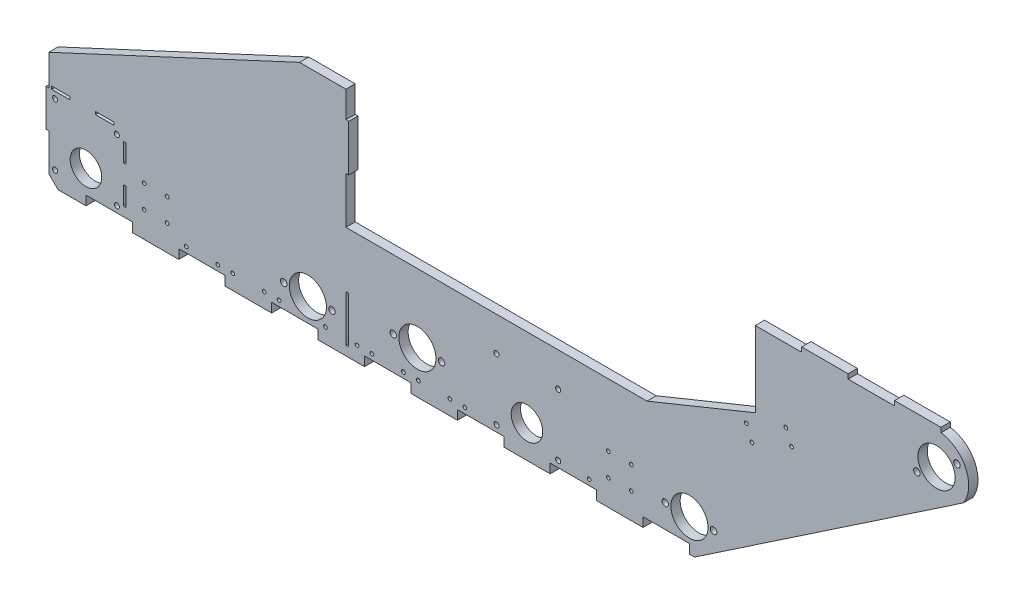
SolidWorks part; units mm, degrees
material "아크릴(내충격성)"
ref_plane "정면" through (0, 0, 0) normal (0, 0, 1) x (1, 0, 0)
ref_plane "윗면" through (0, 0, 0) normal (0, 1, 0) x (1, 0, 0)
ref_plane "우측면" through (0, 0, 0) normal (1, 0, 0) x (0, 0, -1)
sketch "스케치1" plane through (0, 0, 0) normal (0, 0, 1) x (1, 0, 0)
  line L0 (35.3016, 38.2586) -> (35.3016, -130.1494) construction
  line L3 (5.2676, -97.6555) -> (35.3016, -97.6555)
  line L5 (-42.9653, -47.6555) -> (113.7321, -47.6555) construction
  line L6 (-13.0327, -95.9898) -> (35.3016, -47.6555) construction
  line L7 (360.3016, 61.656) -> (360.3016, -136.4824) construction
  line L10 (685.3016, -62.6555) -> (510.3016, -62.6555) construction
  line L11 (510.3016, -62.6555) -> (470.1121, -62.6555) construction
  line L12 (652.0676, -14.4224) -> (652.0676, -80.8905) construction
  line L13 (2.0676, -14.4224) -> (2.0676, -80.8905) construction
  line L14 (510.3016, -62.6555) -> (951.4227, 116.8455) construction
  line L15 (639.5932, 22.3445) -> (956.2142, 151.1839)
  line L16 (685.3016, -62.6555) -> (951.4227, 116.8455) construction
  line L17 (35.3016, -62.6555) -> (274.3016, -62.6555) construction
  line L18 (274.3016, -62.6555) -> (392.3016, -62.6555) construction
  line L19 (392.3016, -62.6555) -> (392.3016, -51.6555) construction
  line L20 (347.1794, -51.6555) -> (433.0872, -51.6555) construction
  line L22 (718.5356, -14.4224) -> (456.239, -14.4224) construction
  line L23 (-14.6984, -87.6555) -> (705.4567, -87.6555) construction
  line L24 (685.3016, -62.6555) -> (722.4102, -62.6555) construction
  line L25 (980.3852, 97.7862) -> (690.6311, -97.6555)
  line L26 (35.3016, -97.6555) -> (35.3016, -87.6555)
  line L27 (231.5316, 22.3445) -> (231.5316, -97.6555) construction
  line L28 (35.3016, -87.6555) -> (85.3016, -87.6555)
  line L29 (182.7916, 22.3445) -> (182.7916, -87.6555) construction
  line L30 (85.3016, -87.6555) -> (85.3016, -97.6555)
  line L34 (135.3016, -97.6555) -> (135.3016, -87.6555)
  line L38 (231.5316, -97.6555) -> (235.3016, -97.6555)
  line L39 (135.2976, -97.6555) -> (135.3016, -97.6555)
  line L40 (135.3016, -87.6555) -> (185.3016, -87.6555)
  line L41 (185.3016, -87.6555) -> (185.3016, -97.6555)
  line L42 (85.3056, -97.6555) -> (135.2976, -97.6555)
  line L43 (185.3016, -97.6555) -> (231.5316, -97.6555)
  line L44 (235.3016, -97.6555) -> (235.3016, -87.6555)
  line L45 (235.3016, -87.6555) -> (285.3016, -87.6555)
  line L46 (285.3016, -87.6555) -> (285.3016, -97.6555)
  line L47 (335.3016, -97.6555) -> (335.3016, -87.6555)
  line L48 (335.3016, -87.6555) -> (385.3016, -87.6555)
  line L49 (385.3016, -87.6555) -> (385.3016, -97.6555)
  line L50 (435.3016, -97.6555) -> (435.3016, -87.6555)
  line L51 (435.3016, -87.6555) -> (485.3016, -87.6555)
  line L52 (485.3016, -87.6555) -> (485.3016, -97.6555)
  line L53 (535.3016, -97.6555) -> (535.3016, -87.6555)
  line L54 (535.3016, -87.6555) -> (585.3016, -87.6555)
  line L55 (585.3016, -87.6555) -> (585.3016, -97.6555)
  line L56 (635.3016, -97.6555) -> (635.3016, -87.6555)
  line L57 (635.3016, -87.6555) -> (685.3016, -87.6555)
  line L58 (685.3016, -87.6555) -> (685.3016, -97.6555)
  line L59 (85.3016, -97.6555) -> (85.3056, -97.6555)
  line L60 (285.3016, -97.6555) -> (335.3016, -97.6555)
  line L61 (385.3016, -97.6555) -> (435.3016, -97.6555)
  line L62 (485.3016, -97.6555) -> (535.3016, -97.6555)
  line L63 (585.3016, -97.6555) -> (635.3016, -97.6555)
  line L64 (685.3016, -97.6555) -> (690.6311, -97.6555)
  line L65 (-25.5762, -81.6555) -> (758.4959, -81.6555) construction
  line L66 (110.3016, -97.6555) -> (110.3016, -39.5812) construction
  line L71 (110.3016, -57.6555) -> (92.8016, -57.6555) construction
  line L72 (110.3016, -57.6555) -> (97.9272, -45.2811) construction
  line L73 (610.3016, -97.6555) -> (610.3016, -39.5812) construction
  line L74 (610.3016, -57.6555) -> (592.8016, -57.6555) construction
  line L75 (610.3016, -57.6555) -> (597.9272, -45.2811) construction
  line L76 (-14.6984, -7.4224) -> (81.4007, -7.4224) construction
  line L77 (75.5356, -87.6555) -> (75.5356, 5.7003) construction
  line L78 (315.3016, 122.6616) -> (315.3016, 146.501)
  line L79 (-11.6984, -97.6555) -> (-11.6984, -7.4224) construction
  line L87 (315.3016, -97.6555) -> (315.3016, 22.3445) construction
  line L88 (-1.6984, -7.4224) -> (18.3016, -7.4224)
  line L89 (-1.6984, -7.4224) -> (-1.6984, -4.4224)
  line L90 (-1.6984, -4.4224) -> (18.3016, -4.4224)
  line L91 (18.3016, -7.4224) -> (18.3016, -4.4224)
  line L92 (65.5356, -7.4224) -> (45.5356, -7.4224)
  line L93 (65.5356, -7.4224) -> (65.5356, -4.4224)
  line L94 (65.5356, -4.4224) -> (45.5356, -4.4224)
  line L95 (45.5356, -7.4224) -> (45.5356, -4.4224)
  line L96 (75.5356, -17.4224) -> (78.6964, -17.4224)
  line L97 (75.5356, -17.4224) -> (75.5356, -37.4224)
  line L98 (75.5356, -37.4224) -> (78.6964, -37.4224)
  line L99 (78.6964, -17.4224) -> (78.6964, -37.4224)
  line L100 (75.5356, -77.6555) -> (78.6964, -77.6555)
  line L101 (75.5356, -77.6555) -> (75.5356, -57.6555)
  line L102 (75.5356, -57.6555) -> (78.6964, -57.6555)
  line L103 (78.6964, -77.6555) -> (78.6964, -57.6555)
  line L104 (321.0516, -97.6555) -> (321.0516, -72.2502) construction
  line L105 (315.3016, 22.3445) -> (315.3016, 151.1839) construction
  line L114 (315.3016, 151.1839) -> (956.2142, 151.1839) construction
  line L115 (315.3016, 22.3445) -> (315.3016, 72.6616)
  line L118 (315.3016, 22.3445) -> (639.5932, 22.3445)
  line L121 (315.3016, -87.6555) -> (318.3016, -87.6555)
  line L122 (315.3016, -87.6555) -> (315.3016, -37.6555)
  line L123 (315.3016, -37.6555) -> (318.3016, -37.6555)
  line L124 (318.3016, -87.6555) -> (318.3016, -37.6555)
  line L125 (315.3016, 72.6616) -> (318.3016, 72.6616)
  line L127 (315.3016, 122.6616) -> (318.3016, 122.6616)
  line L128 (318.3016, 72.6616) -> (318.3016, 122.6616)
  line L130 (315.3016, 146.501) -> (315.3016, 151.1839)
  line L131 (315.3016, 151.1839) -> (265.2997, 151.1839)
  line L132 (265.2997, 151.1839) -> (-4.7324, 25.5846)
  line L133 (-4.7324, -97.6555) -> (-4.7324, 25.5846) construction
  line L135 (-4.7324, -87.6555) -> (5.2676, -97.6555)
  line L136 (-7.7324, -97.6555) -> (-7.7324, 24.1892) construction
  line L139 (-4.7324, -87.6555) -> (-4.7324, -47.6895)
  line L140 (-4.7324, -47.6895) -> (-7.7324, -47.6895)
  line L141 (-7.7324, -47.6895) -> (-7.7324, -7.6895)
  line L142 (-7.7324, -7.6895) -> (-4.7324, -7.6895)
  line L143 (-4.7324, -7.6895) -> (-4.7324, 25.5846)
  circle A1 centre (2.0676, -80.8905) radius 2.75
  circle A5 centre (2.0676, -14.4224) radius 2.75
  circle A6 centre (68.5356, -14.4224) radius 2.75
  circle A7 centre (68.5356, -80.8905) radius 2.75
  circle A12 centre (35.3016, -62.6555) radius 17
  circle A13 centre (685.3016, -62.6555) radius 20
  circle A14 centre (951.4227, 116.8455) radius 20
  circle A15 centre (973.4042, 130.7311) radius 3.5
  circle A16 centre (930.3015, 101.6831) radius 3.5
  arc A18 (980.3852, 97.7862) -> (956.2142, 151.1839) centre (951.4227, 116.8455) ccw
  circle A22 centre (274.3016, -62.6555) radius 20
  circle A23 centre (248.3016, -62.6555) radius 3.5
  circle A24 centre (300.3016, -62.6555) radius 3.5
  circle A25 centre (392.3016, -51.6555) radius 20
  circle A26 centre (366.3016, -51.6555) radius 3.5
  circle A27 centre (418.3016, -51.6555) radius 3.5
  circle A28 centre (543.8987, -14.4224) radius 2.75
  circle A29 centre (477.4307, -14.4224) radius 2.75
  circle A30 centre (477.4307, -80.8905) radius 2.75
  circle A31 centre (543.8987, -80.8905) radius 2.75
  circle A32 centre (510.3016, -62.6555) radius 17
  circle A33 centre (659.3016, -62.6555) radius 3.5
  circle A34 centre (711.3016, -62.6555) radius 3.5
  circle A37 centre (143.3016, -81.6555) radius 2
  circle A38 centre (177.3016, -81.6555) radius 2
  circle A39 centre (193.3016, -81.6555) radius 2
  circle A40 centre (227.3016, -81.6555) radius 2
  circle A41 centre (243.3016, -81.6555) radius 2
  circle A43 centre (293.3016, -81.6555) radius 2
  circle A44 centre (327.3016, -81.6555) radius 2
  circle A45 centre (343.3016, -81.6555) radius 2
  circle A46 centre (377.3016, -81.6555) radius 2
  circle A47 centre (393.3016, -81.6555) radius 2
  circle A48 centre (427.3016, -81.6555) radius 2
  circle A49 centre (443.3016, -81.6555) radius 2
  circle A54 centre (577.3016, -81.6555) radius 2
  circle A67 centre (97.9272, -45.2811) radius 2
  circle A68 centre (122.676, -45.2811) radius 2
  circle A69 centre (122.676, -70.0298) radius 2
  circle A70 centre (97.9272, -70.0298) radius 2
  circle A72 centre (597.9272, -45.2811) radius 2
  circle A73 centre (622.676, -45.2811) radius 2
  circle A74 centre (622.676, -70.0298) radius 2
  circle A75 centre (597.9272, -70.0298) radius 2
  point P22 (28.6519, -47.9736)
  point P25 (35.3016, -47.6565)
  point P53 (730.8621, 27.095)
  dimension "D3" = 175
  dimension "D5" = 4
  dimension "D9" = 34
  dimension "D10" = 26
  dimension "D12" = 7
  dimension "D13" = 40
  dimension "D14" = 7
  dimension "D20" = 33.235
  dimension "D22" = 7
  dimension "D23" = 7
  dimension "D29" = 26
  dimension "D7" = 40
  dimension "D39" = 40
  dimension "D42" = 40
  dimension "D43" = 45
  dimension "D47" = 7
  dimension "D45" = 3
  dimension "D48" = 25
  dimension "D4" = 45
  dimension "D6" = 325
  dimension "D8" = 15
  dimension "D11" = 321
  dimension "D15" = 26
  dimension "D16" = 26
  dimension "D17" = 26
  dimension "D18" = 66.468
  dimension "D19" = 30
  dimension "D21" = 35
  dimension "D24" = 26
  dimension "D25" = 239
  dimension "D26" = 26
  dimension "D27" = 118
  dimension "D28" = 11
  dimension "D30" = 26
  dimension "D32" = 10
  dimension "D33" = 16.77
  dimension "D34" = 50
  dimension "D35" = 48.74
  dimension "D37" = 7
  dimension "D38" = 6
  dimension "D40" = 49.996
  dimension "D41" = 45
  dimension "D44" = 3
  dimension "D46" = 7
  dimension "D50" = 10
  dimension "D51" = 20
  dimension "D52" = 20
  dimension "D53" = 10
  dimension "D54" = 10
  dimension "D55" = 20
  dimension "D56" = 20
  dimension "D57" = 15
  dimension "D58" = 6.25
  dimension "D59" = 8
  dimension "D60" = 3
  dimension "D61" = 50
extrude "보스-돌출1" add sketch "스케치1" along normal blind 10
sketch "스케치2" plane through (0, 0, 10) normal (0, 0, 1) x (1, 0, 0)
  line L2 (756.2142, 151.1839) -> (756.2142, 69.7999)
  line L3 (956.2142, 151.1839) -> (639.5932, 22.3445) construction
  line L4 (757.4592, 156.1839) -> (983.3519, 156.1839) construction
  line L5 (806.2142, 151.1839) -> (806.2142, 156.1839)
  line L6 (806.2142, 156.1839) -> (856.2142, 156.1839)
  line L7 (856.2142, 156.1839) -> (856.2142, 151.1839)
  line L8 (906.2142, 151.1839) -> (906.2142, 156.1839)
  line L9 (906.2142, 156.1839) -> (956.2142, 156.1839)
  line L11 (806.2142, 151.1839) -> (756.2142, 151.1839)
  line L12 (906.2142, 151.1839) -> (856.2142, 151.1839)
  line L13 (956.2142, 156.1839) -> (956.2142, 151.1839)
  line L14 (956.2142, 151.1839) -> (756.2142, 69.7999)
  line L15 (756.2142, 151.1839) -> (756.2142, 201.5102) construction
  line L16 (265.2997, 151.1839) -> (756.2142, 151.1839) construction
  dimension "D1" = 50
  dimension "D2" = 81.384
  dimension "D3" = 50
  dimension "D4" = 50
  dimension "D5" = 50
  dimension "D6" = 5
  dimension "D7" = 5
  dimension "D8" = 5
extrude "보스-돌출3" add sketch "스케치2" against normal blind 10
sketch "스케치3" plane through (0, 0, 10) normal (0, 0, 1) x (1, 0, 0)
  line L0 (491.1525, -16.4677) -> (932.5771, 163.1579) construction
  line L1 (598.2558, 2.2837) -> (833.1912, 97.8842) construction
  line L2 (642.8706, -22.7464) -> (861.9919, 66.419) construction
  line L3 (696.3835, 67.0454) -> (718.379, 12.9923) construction
  line L4 (816.7959, 116.044) -> (841.4558, 55.4431) construction
  line L5 (651.9839, 16.6759) -> (881.2925, 109.9867) construction
  line L6 (777.8935, 100.2137) -> (800.5201, 44.6094) construction
  line L7 (756.5897, 91.5447) -> (779.5403, 35.1444) construction
  line L8 (735.286, 82.8757) -> (756.6675, 30.3313) construction
  line L9 (712.1807, 23.8974) -> (847.6453, 79.021) construction
  circle A1 centre (510.3016, -62.6555) radius 50
  circle A8 centre (951.4227, 116.8455) radius 50
  circle A9 centre (746.5632, 55.1624) radius 2
  circle A10 centre (752.5938, 40.3424) radius 2
  circle A11 centre (789.1707, 72.5003) radius 2
  circle A12 centre (795.2012, 57.6803) radius 2
  dimension "D5" = 100
  dimension "D6" = 100
  dimension "D1" = 23
  dimension "D2" = 40
  dimension "D3" = 130
  dimension "D4" = 125
  dimension "D7" = 6.92
  dimension "D8" = 65
  dimension "D9" = 23
  dimension "D10" = 23
  dimension "D11" = 16
extrude "컷-돌출1" cut sketch "스케치3" against normal through all contours A10 | A9 | A11 | A12
sketch "스케치4" [suppressed] plane through (0, 0, 10) normal (0, 0, 1) x (1, 0, 0)
  line L0 (510.3016, -112.6555) -> (685.3016, -112.6555)
  line L1 (491.4561, -16.343) -> (932.5772, 163.158)
  line L2 (713.2612, -104.1073) -> (979.3823, 75.3936)
  line L3 (510.3016, -62.6555) -> (685.3016, -62.6555) construction
  line L4 (951.4227, 116.8455) -> (951.4227, -62.6555) construction
  circle A0 centre (510.3016, -62.6555) radius 50
  circle A1 centre (951.4227, 116.8455) radius 50
  circle A2 centre (685.3016, -62.6555) radius 50
  dimension "D1" = 100
  dimension "D2" = 100
  dimension "D3" = 100
